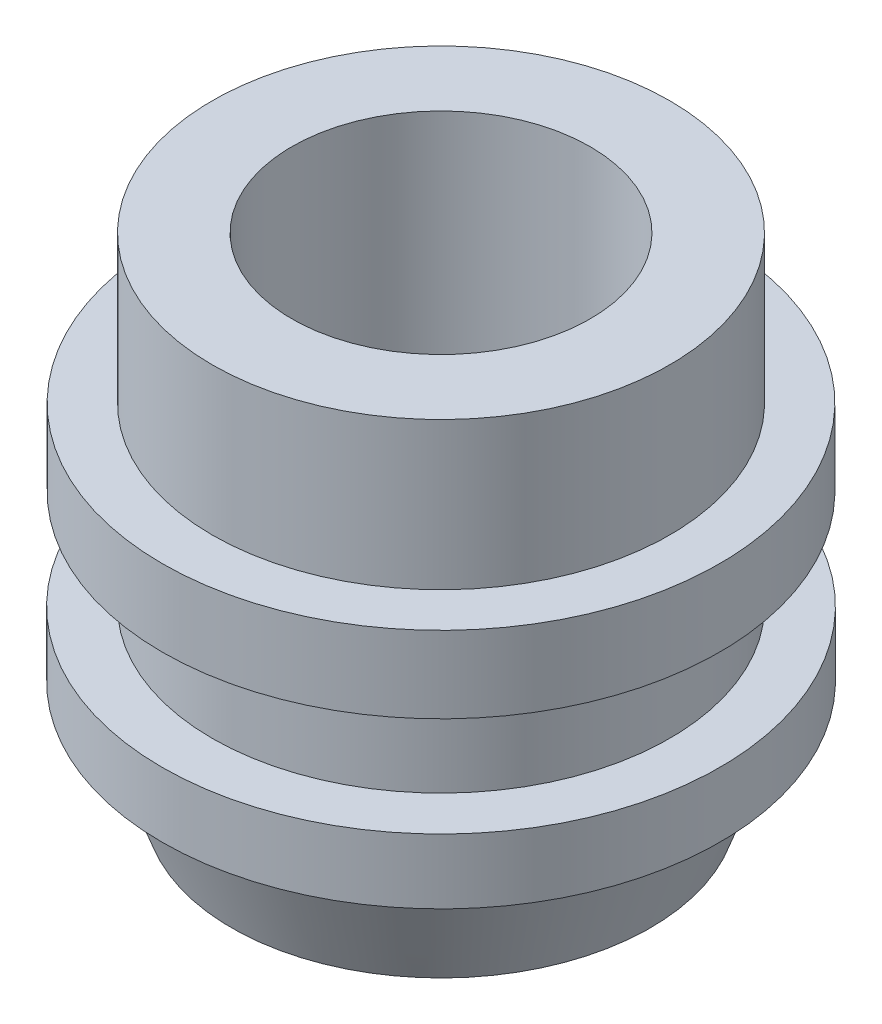
SolidWorks part; units mm, degrees
ref_plane "前视基准面" through (0, 0, 0) normal (0, 0, 1) x (1, 0, 0)
ref_plane "上视基准面" through (0, 0, 0) normal (0, 1, 0) x (1, 0, 0)
ref_plane "右视基准面" through (0, 0, 0) normal (1, 0, 0) x (0, 0, -1)
sketch "草图2" plane through (0, 0, 0) normal (1, 0, 0) x (0, 0, -1)
  line L0 (0, 0) -> (0, 7.0956) construction
  line L1 (1.5, -0.1962) -> (1.5, 4.8038)
  line L2 (1.5, 4.8038) -> (2.3, 4.8038)
  line L3 (2.3, 4.8038) -> (2.3, 3.3218)
  line L4 (2.3, 3.3218) -> (2.8, 3.3218)
  line L5 (2.8, 3.3218) -> (2.8, 2.5512)
  line L6 (2.8, 2.5512) -> (2.3, 2.5512)
  line L7 (2.3, 2.5512) -> (2.3, 1.5512)
  line L8 (2.3, 1.5512) -> (2.8039, 1.5512)
  line L9 (2.8039, 1.5512) -> (2.8039, 0.8992)
  line L10 (2.8039, 0.8992) -> (2.5039, 0.8992)
  line L11 (2.5039, 0.8992) -> (2.1052, -0.1962)
  line L12 (2.1052, -0.1962) -> (1.5, -0.1962)
  line L13 (2.3, 2.5512) -> (2.3, 3.3218) construction
  point P9 (2.3, 3.3366)
  dimension "D1" = 1.4819
  dimension "D2" = 0.7706
  dimension "D3" = 1
  dimension "D4" = 0.652
  dimension "D5" = 20
  dimension "D6" = 5
  dimension "D7" = 0.8
  dimension "D8" = 0.5
  dimension "D9" = 0.5039
  dimension "D10" = 0.3
  dimension "D11" = 1.5
revolve "旋转1" add sketch "草图2" angle 360 about L0
